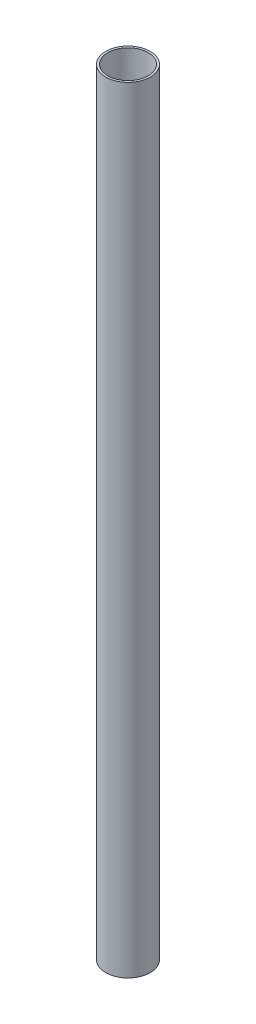
SolidWorks part; units mm, degrees
material "6061-T6 (SS)"
ref_plane "Front Plane" through (0, 0, 0) normal (0, 0, 1) x (1, 0, 0)
ref_plane "Top Plane" through (0, 0, 0) normal (0, 1, 0) x (1, 0, 0)
ref_plane "Right Plane" through (0, 0, 0) normal (1, 0, 0) x (0, 0, -1)
sketch "Sketch1" plane through (0, 0, 0) normal (0, 1, 0) x (1, 0, 0)
  circle A0 centre (0, 0) radius 15.875
  circle A1 centre (0, 0) radius 14.351
  dimension "D1" = 31.75
  dimension "D2" = 1.524
extrude "Boss-Extrude1" add sketch "Sketch1" along normal blind 552.45 contours A0 | A1
